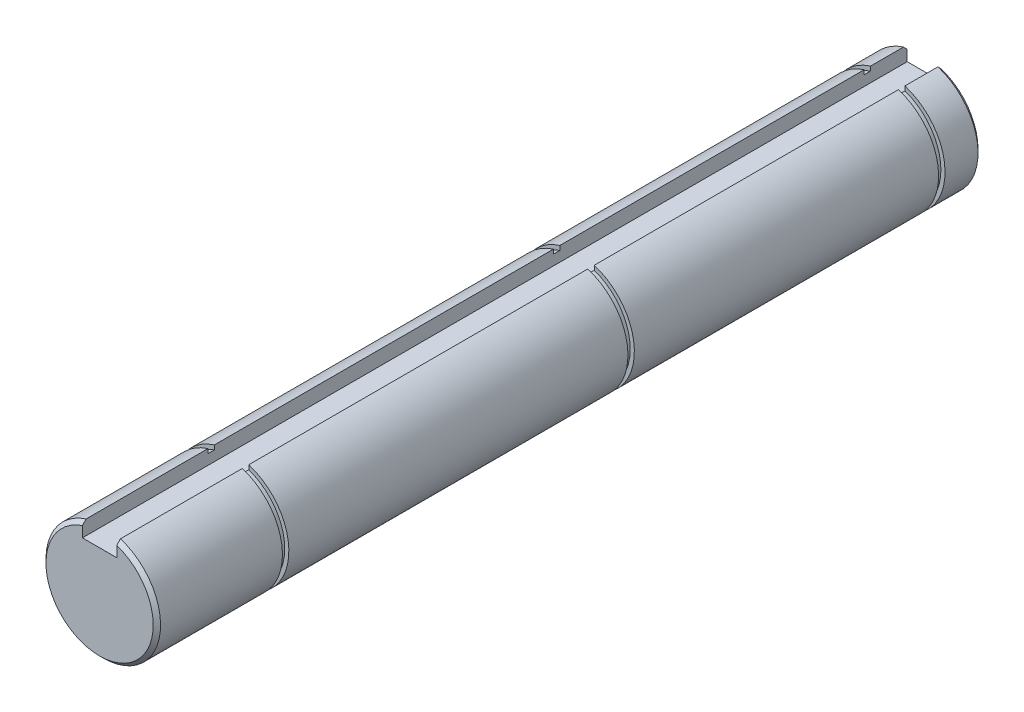
SolidWorks part; units mm, degrees
material "Chrome Stainless Steel"
ref_plane "Front Plane" through (0, 0, 0) normal (0, 0, 1) x (1, 0, 0)
ref_plane "Top Plane" through (0, 0, 0) normal (0, 1, 0) x (1, 0, 0)
ref_plane "Right Plane" through (0, 0, 0) normal (1, 0, 0) x (0, 0, -1)
sketch "Sketch1" plane through (0, 0, 0) normal (0, 0, 1) x (1, 0, 0)
  line L1 (2.3812, 10.3188) -> (-2.3813, 10.3188)
  line L2 (2.3812, 10.3188) -> (2.3812, 5.5563)
  line L3 (2.3812, 5.5563) -> (-2.3813, 5.5563)
  line L4 (-2.3813, 10.3188) -> (-2.3813, 5.5563)
  line L5 (2.3812, 10.3188) -> (-2.3813, 5.5563) construction
  line L6 (2.3812, 5.5563) -> (-2.3813, 10.3188) construction
  circle A0 centre (0, 0) radius 7.9375
  point P3 (0, 7.9375)
  dimension "D1" = 15.875
  dimension "D2" = 4.7625
  dimension "D3" = 4.7625
extrude "Boss-Extrude1" add sketch "Sketch1" along normal blind 114.3 contours L4 A0 L2 L3
chamfer "Chamfer1" distance 0.508 angle 45 2 edges at (0, -7.9375, 114.3) (0, -7.9375, 0)
ref_plane "Plane1" through (0, 0, 5.08) normal (0, 0, -1) x (-1, 0, 0)
sketch "Sketch2" plane through (0, 0, 5.08) normal (0, 0, -1) x (-1, 0, 0)
  circle A0 centre (0, 0) radius 7.366
  circle A1 centre (0, 0) radius 8.6978
  dimension "D1" = 14.732
extrude "Cut-Extrude1" cut sketch "Sketch2" against normal blind 0.889
ref_plane "Plane2" through (0, 0, 49.022) normal (0, 0, 1) x (1, 0, 0)
ref_plane "Plane3" through (0, 0, 96.901) normal (0, 0, 1) x (1, 0, 0)
sketch "Sketch3" plane through (0, 0, 49.022) normal (0, 0, 1) x (1, 0, 0)
  circle A0 centre (0, 0) radius 7.366
  dimension "D1" = 14.732
extrude "Cut-Extrude2" cut sketch "Sketch3" against normal blind 0.889 flip side to cut
sketch "Sketch4" plane through (0, 0, 96.901) normal (0, 0, 1) x (1, 0, 0)
  circle A0 centre (0, 0) radius 7.366
  dimension "D1" = 14.732
extrude "Cut-Extrude3" cut sketch "Sketch4" against normal blind 0.889 flip side to cut
